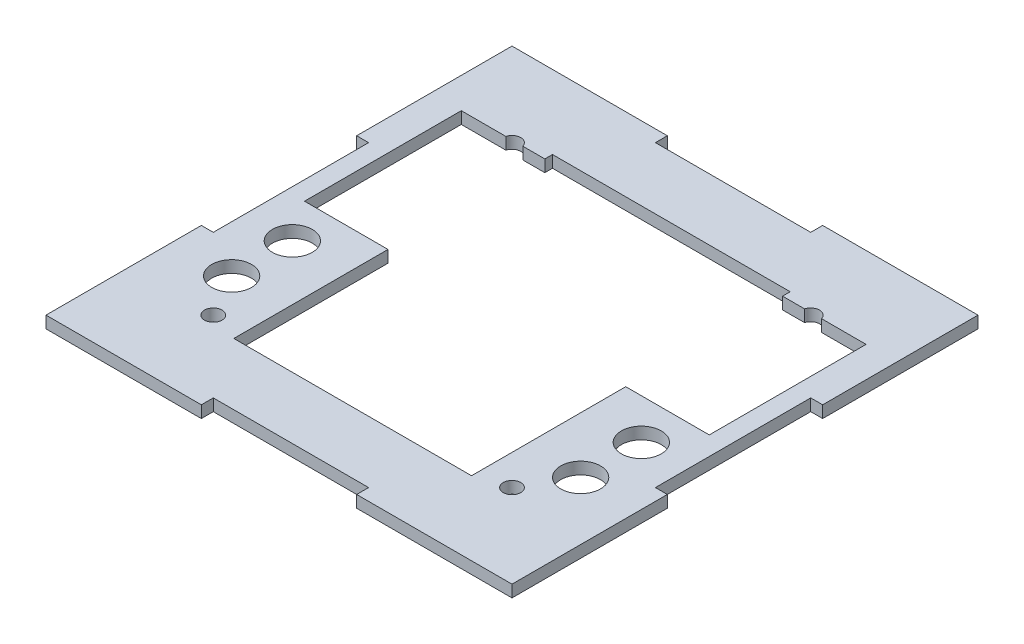
SolidWorks part; units mm, degrees
ref_plane "Front Plane" through (0, 0, 0) normal (0, 0, 1) x (1, 0, 0)
ref_plane "Top Plane" through (0, 0, 0) normal (0, 1, 0) x (1, 0, 0)
ref_plane "Right Plane" through (0, 0, 0) normal (1, 0, 0) x (0, 0, -1)
sketch "Sketch1" plane through (0, 0, 0) normal (0, 1, 0) x (1, 0, 0)
  line L0 (-58.5, 19.5) -> (-58.5, 58.5)
  line L1 (-58.5, -58.5) -> (58.5, -58.5) construction
  line L2 (-58.5, -58.5) -> (-58.5, 58.5) construction
  line L3 (-58.5, 58.5) -> (58.5, 58.5) construction
  line L4 (58.5, -58.5) -> (58.5, 58.5) construction
  line L5 (-58.5, -58.5) -> (58.5, 58.5) construction
  line L6 (-58.5, 58.5) -> (58.5, -58.5) construction
  line L7 (-55.5, -55.5) -> (55.5, -55.5) construction
  line L8 (-55.5, -55.5) -> (-55.5, 55.5) construction
  line L9 (-55.5, 55.5) -> (55.5, 55.5) construction
  line L10 (55.5, -55.5) -> (55.5, 55.5) construction
  line L11 (-55.5, -55.5) -> (55.5, 55.5) construction
  line L12 (-55.5, 55.5) -> (55.5, -55.5) construction
  line L13 (-58.5, 58.5) -> (-19.5, 58.5)
  line L14 (-19.5, 58.5) -> (-19.5, 55.5)
  line L15 (-19.5, 55.5) -> (19.5, 55.5)
  line L16 (19.5, 55.5) -> (19.5, 58.5)
  line L17 (19.5, 58.5) -> (58.5, 58.5)
  line L18 (58.5, 58.5) -> (58.5, 19.5)
  line L19 (58.5, 19.5) -> (55.5, 19.5)
  line L20 (55.5, 19.5) -> (55.5, -19.5)
  line L21 (55.5, -19.5) -> (58.5, -19.5)
  line L22 (58.5, -19.5) -> (58.5, -58.5)
  line L23 (58.5, -58.5) -> (19.5, -58.5)
  line L24 (19.5, -58.5) -> (19.5, -55.5)
  line L25 (19.5, -55.5) -> (-19.5, -55.5)
  line L26 (-19.5, -55.5) -> (-19.5, -58.5)
  line L27 (-19.5, -58.5) -> (-58.5, -58.5)
  line L28 (-58.5, -58.5) -> (-58.5, -19.5)
  line L29 (-58.5, -19.5) -> (-55.5, -19.5)
  line L30 (-55.5, -19.5) -> (-55.5, 19.5)
  line L31 (-55.5, 19.5) -> (-58.5, 19.5)
  circle A0 centre (-37.5, 37.5) radius 2.2
  circle A1 centre (37.5, 37.5) radius 2.2
  circle A2 centre (37.5, -37.5) radius 2.2
  circle A3 centre (-37.5, -37.5) radius 2.2
  point P0 (0, 0)
  point P6 (0, 0)
  dimension "D3" = 4.4
  dimension "D1" = 117
  dimension "D2" = 111
  dimension "D4" = 75
extrude "Boss-Extrude1" add sketch "Sketch1" along normal blind 3
sketch "Sketch3" plane through (0, 3, 0) normal (0, 1, 0) x (1, 0, 0)
  line L0 (0, -0.635) -> (0, 0.635) construction
  line L1 (-9.525, 20.955) -> (9.525, 20.955)
  line L2 (-9.525, 20.955) -> (-9.525, 40.005)
  line L3 (-9.525, 40.005) -> (9.525, 40.005)
  line L4 (9.525, 20.955) -> (9.525, 40.005)
  line L5 (-9.525, 20.955) -> (9.525, 40.005) construction
  line L6 (-9.525, 40.005) -> (9.525, 20.955) construction
  line L7 (-9.525, 0.635) -> (9.525, 0.635)
  line L8 (-9.525, 0.635) -> (-9.525, 19.685)
  line L9 (-9.525, 19.685) -> (9.525, 19.685)
  line L10 (9.525, 0.635) -> (9.525, 19.685)
  line L11 (-9.525, 0.635) -> (9.525, 19.685) construction
  line L12 (-9.525, 19.685) -> (9.525, 0.635) construction
  line L13 (-9.525, -19.685) -> (9.525, -19.685)
  line L14 (-9.525, -19.685) -> (-9.525, -0.635)
  line L15 (-9.525, -0.635) -> (9.525, -0.635)
  line L16 (9.525, -19.685) -> (9.525, -0.635)
  line L17 (-9.525, -19.685) -> (9.525, -0.635) construction
  line L18 (-9.525, -0.635) -> (9.525, -19.685) construction
  line L19 (-9.525, -40.005) -> (9.525, -40.005)
  line L20 (-9.525, -40.005) -> (-9.525, -20.955)
  line L21 (-9.525, -20.955) -> (9.525, -20.955)
  line L22 (9.525, -40.005) -> (9.525, -20.955)
  line L23 (-9.525, -40.005) -> (9.525, -20.955) construction
  line L24 (-9.525, -20.955) -> (9.525, -40.005) construction
  line L25 (-29.845, 20.955) -> (-29.845, 40.005)
  line L26 (-29.845, 20.955) -> (-10.795, 20.955)
  line L27 (-10.795, 20.955) -> (-10.795, 40.005)
  line L28 (-29.845, 40.005) -> (-10.795, 40.005)
  line L29 (-29.845, 0.635) -> (-29.845, 19.685)
  line L30 (-29.845, 0.635) -> (-10.795, 0.635)
  line L31 (-10.795, 0.635) -> (-10.795, 19.685)
  line L32 (-29.845, 19.685) -> (-10.795, 19.685)
  line L33 (-29.845, -19.685) -> (-29.845, -0.635)
  line L34 (-29.845, -19.685) -> (-10.795, -19.685)
  line L35 (-10.795, -19.685) -> (-10.795, -0.635)
  line L36 (-29.845, -0.635) -> (-10.795, -0.635)
  line L37 (-29.845, -40.005) -> (-29.845, -20.955)
  line L38 (-29.845, -40.005) -> (-10.795, -40.005)
  line L39 (-10.795, -40.005) -> (-10.795, -20.955)
  line L40 (-29.845, -20.955) -> (-10.795, -20.955)
  line L41 (-9.525, 20.955) -> (-9.525, 40.005)
  line L42 (-9.525, 20.955) -> (9.525, 20.955)
  line L43 (9.525, 20.955) -> (9.525, 40.005)
  line L44 (-9.525, 40.005) -> (9.525, 40.005)
  line L45 (-9.525, 0.635) -> (-9.525, 19.685)
  line L46 (-9.525, 0.635) -> (9.525, 0.635)
  line L47 (9.525, 0.635) -> (9.525, 19.685)
  line L48 (-9.525, 19.685) -> (9.525, 19.685)
  line L49 (-9.525, -19.685) -> (-9.525, -0.635)
  line L50 (-9.525, -19.685) -> (9.525, -19.685)
  line L51 (9.525, -19.685) -> (9.525, -0.635)
  line L52 (-9.525, -0.635) -> (9.525, -0.635)
  line L53 (-9.525, -40.005) -> (-9.525, -20.955)
  line L54 (-9.525, -40.005) -> (9.525, -40.005)
  line L55 (9.525, -40.005) -> (9.525, -20.955)
  line L56 (-9.525, -20.955) -> (9.525, -20.955)
  line L57 (10.795, 20.955) -> (10.795, 40.005)
  line L58 (10.795, 20.955) -> (29.845, 20.955)
  line L59 (29.845, 20.955) -> (29.845, 40.005)
  line L60 (10.795, 40.005) -> (29.845, 40.005)
  line L61 (10.795, 0.635) -> (10.795, 19.685)
  line L62 (10.795, 0.635) -> (29.845, 0.635)
  line L63 (29.845, 0.635) -> (29.845, 19.685)
  line L64 (10.795, 19.685) -> (29.845, 19.685)
  line L65 (10.795, -19.685) -> (10.795, -0.635)
  line L66 (10.795, -19.685) -> (29.845, -19.685)
  line L67 (29.845, -19.685) -> (29.845, -0.635)
  line L68 (10.795, -0.635) -> (29.845, -0.635)
  line L69 (10.795, -40.005) -> (10.795, -20.955)
  line L70 (10.795, -40.005) -> (29.845, -40.005)
  line L71 (29.845, -40.005) -> (29.845, -20.955)
  line L72 (10.795, -20.955) -> (29.845, -20.955)
  line L73 (-58.5, -58.5) -> (58.5, 58.5) construction
  line L74 (-31.765, 17.765) -> (-31.765, -1.285)
  line L79 (-31.765, 38.085) -> (-50.815, 38.085)
  line L80 (-31.765, 38.085) -> (-31.765, 19.035)
  line L81 (-31.765, 19.035) -> (-50.815, 19.035)
  line L82 (-50.815, 38.085) -> (-50.815, 19.035)
  line L83 (-31.765, 17.765) -> (-50.815, 17.765)
  line L84 (-50.815, 17.765) -> (-50.815, -1.285)
  line L85 (-31.765, -1.285) -> (-50.815, -1.285)
  line L86 (50.815, 17.765) -> (50.815, -1.285)
  line L87 (50.815, 17.765) -> (31.765, 17.765)
  line L88 (31.765, 17.765) -> (31.765, -1.285)
  line L89 (50.815, -1.285) -> (31.765, -1.285)
  line L90 (50.815, 38.085) -> (50.815, 19.035)
  line L91 (50.815, 38.085) -> (31.765, 38.085)
  line L92 (31.765, 38.085) -> (31.765, 19.035)
  line L93 (50.815, 19.035) -> (31.765, 19.035)
  circle A0 centre (43.9018, -26.6721) radius 5
  circle A1 centre (-43.7182, -26.6721) radius 5
  circle A2 centre (-43.7182, -11.4321) radius 5
  circle A3 centre (43.9018, -11.4321) radius 5
  point P0 (0, 30.48)
  point P5 (0, 10.16)
  point P10 (0, -10.16)
  point P15 (0, -30.48)
  point P24 (0, 0)
  point P76 (0, 0)
  point P77 (39.0018, -32.1721)
  circle M25 centre (-37.5, 37.5) radius 2.2
  circle M26 centre (37.5, 37.5) radius 2.2
  dimension "D17" = 10
  dimension "D1" = 19.05
  dimension "D2" = 20.32
  dimension "D3" = 20.32
  dimension "D4" = 20.32
  dimension "D7" = 1.92
  dimension "D8" = 1.92
  dimension "D9" = 19.05
  dimension "D10" = 19.05
  dimension "D13" = 12.05
  dimension "D14" = 14.48
  dimension "D15" = 5.5
  dimension "D16" = 4.9
  dimension "D5" = 2
  dimension "D6" = 2
  dimension "D11" = 2
  dimension "D12" = 2
  dimension "D18" = 2
  dimension "D19" = 2
extrude "Cut-Extrude1" cut sketch "Sketch3" against normal through all contours L60 L57 L58 L59 | L64 L61 L62 L63 | L68 L65 L66 L67 | L72 L69 L70 L71 | L19 L22 L21 L20 | L13 L16 L15 L14 | L7 L10 L9 L8 | L1 L4 L3 L2 | L28 L25 L26 L27 | L32 L29 L30 L31 | L36 L33 L34 L35 | L40 L37 L38 L39 | L79 L82 L81 L80 M25 | L85 L74 L83 L84 | L93 L90 L91 L92 M26 | L89 L86 L87 L88 | A2 | A1 | A3 | A0
sketch "Sketch4" plane through (0, 3, 0) normal (0, 1, 0) x (1, 0, 0)
  line L0 (-31.765, -1.285) -> (-29.845, -1.285)
  line L1 (-29.845, -19.685) -> (-29.845, -0.635) construction
  line L2 (-29.845, -1.285) -> (-29.845, -40.005)
  line L3 (-29.845, -40.005) -> (29.845, -40.005)
  line L4 (29.845, -40.005) -> (29.845, -1.285)
  line L5 (29.845, -19.685) -> (29.845, -0.635) construction
  line L6 (29.845, -1.285) -> (50.815, -1.285)
  line L7 (50.815, -1.285) -> (50.815, 38.085)
  line L8 (50.815, 38.085) -> (29.845, 38.085)
  line L9 (29.845, 20.955) -> (29.845, 40.005) construction
  line L10 (29.845, 38.085) -> (10.795, 40.005)
  line L11 (10.795, 40.005) -> (-10.795, 40.005)
  line L12 (-10.795, 40.005) -> (-29.845, 38.085)
  line L13 (-29.845, 20.955) -> (-29.845, 40.005) construction
  line L14 (-29.845, 38.085) -> (-31.765, 38.085)
  line L15 (-31.765, 38.085) -> (-50.815, 19.035)
  line L16 (-50.815, 19.035) -> (-50.815, 17.765)
  line L17 (-50.815, 17.765) -> (-31.765, -1.285)
  line L18 (50.815, -1.285) -> (31.765, -1.285) construction
  point P32 (0, 0)
  point P33 (50.815, -1.285)
  point P36 (-29.845, 38.085)
extrude "Cut-Extrude2" cut sketch "Sketch4" against normal blind 10
